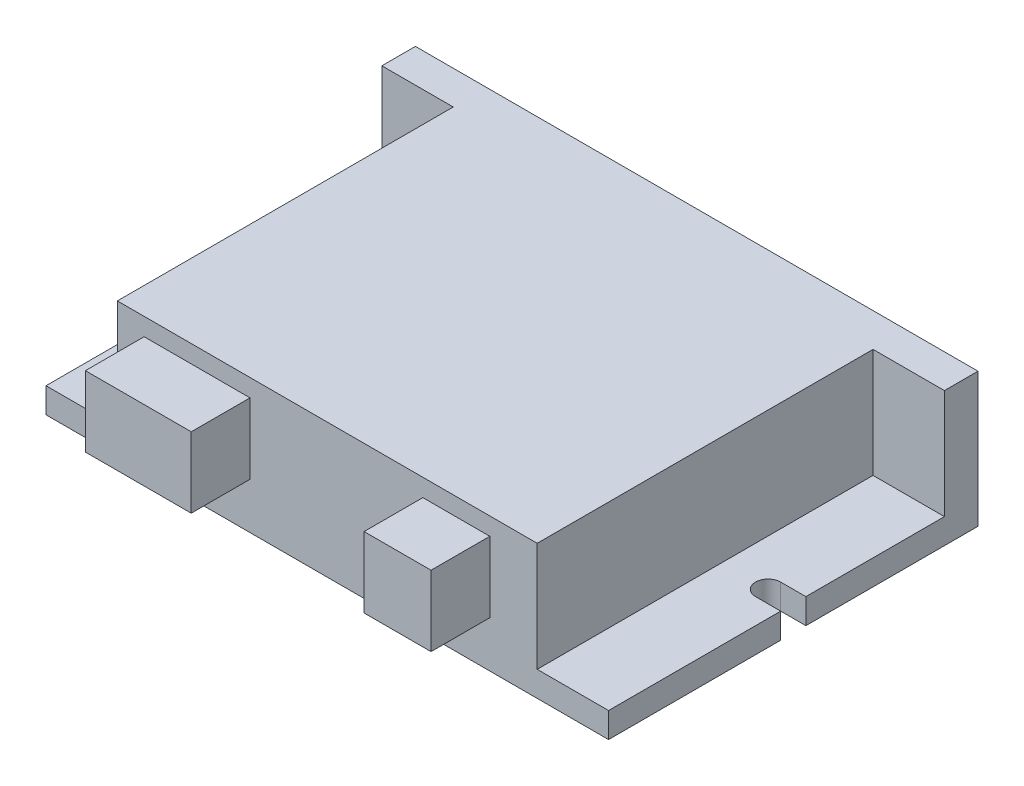
SolidWorks part; units mm, degrees
ref_plane "Front Plane" through (0, 0, 0) normal (0, 0, 1) x (1, 0, 0)
ref_plane "Top Plane" through (0, 0, 0) normal (0, 1, 0) x (1, 0, 0)
ref_plane "Right Plane" through (0, 0, 0) normal (1, 0, 0) x (0, 0, -1)
sketch "Sketch2" plane through (0, 0, 0) normal (0, 1, 0) x (1, 0, 0)
  line L1 (-42.545, -27.94) -> (42.545, -27.94)
  line L2 (-42.545, -27.94) -> (-42.545, 27.94)
  line L3 (-42.545, 27.94) -> (42.545, 27.94)
  line L4 (42.545, -27.94) -> (42.545, 27.94)
  line L5 (-42.545, -27.94) -> (42.545, 27.94) construction
  line L6 (-42.545, 27.94) -> (42.545, -27.94) construction
  point P0 (0, 0)
  dimension "D1" = 55.88
  dimension "D2" = 85.09
extrude "Boss-Extrude1" add sketch "Sketch2" along normal blind 3.81
sketch "Sketch3" plane through (0, 3.81, 0) normal (0, 1, 0) x (1, 0, 0)
  line L0 (-42.545, -27.94) -> (42.545, -27.94) construction
  line L1 (-31.75, -27.94) -> (31.75, -27.94)
  line L2 (-31.75, -27.94) -> (-31.75, 22.86)
  line L3 (-31.75, 22.86) -> (31.75, 22.86)
  line L4 (31.75, -27.94) -> (31.75, 22.86)
  point P6 (0, 22.86)
  dimension "D1" = 50.8
  dimension "D2" = 63.5
extrude "Boss-Extrude2" add sketch "Sketch3" along normal blind 16.51
sketch "Sketch4" plane through (0, 3.81, 0) normal (0, 1, 0) x (1, 0, 0)
  line L0 (42.545, -27.94) -> (42.545, 27.94) construction
  line L1 (-42.545, 27.94) -> (42.545, 27.94)
  line L2 (-42.545, 27.94) -> (-42.545, 22.86)
  line L3 (-42.545, 22.86) -> (42.545, 22.86)
  line L4 (42.545, 27.94) -> (42.545, 22.86)
  line L5 (31.75, 22.86) -> (-31.75, 22.86) construction
extrude "Boss-Extrude3" add sketch "Sketch4" along normal up to surface (16.51 mm away) up to face at (0, 20.32, 2.54)
sketch "Sketch5" plane through (0, 3.81, 0) normal (0, 1, 0) x (1, 0, 0)
  line L0 (38.735, 1.905) -> (42.545, 1.905)
  line L1 (42.545, -27.94) -> (42.545, 22.86) construction
  line L2 (38.735, -1.905) -> (42.545, -1.905)
  line L3 (42.545, 1.905) -> (42.545, -1.905)
  line L4 (0, 36.9467) -> (0, -38.9863) construction
  line L5 (-42.545, 1.905) -> (-42.545, -1.905)
  line L6 (-38.735, -1.905) -> (-42.545, -1.905)
  line L7 (-38.735, 1.905) -> (-42.545, 1.905)
  arc A0 (38.735, 1.905) -> (38.735, -1.905) centre (38.735, 0) ccw
  arc A1 (-38.735, 1.905) -> (-38.735, -1.905) centre (-38.735, 0) cw
  dimension "D1" = 1.905
  dimension "D2" = 3.81
extrude "Cut-Extrude1" cut sketch "Sketch5" against normal through all both and the other way through all
sketch "Sketch6" plane through (0, 0, 27.94) normal (0, 0, 1) x (1, 0, 0)
  line L0 (-42.545, 0) -> (42.545, 0) construction
  line L1 (-27.6993, 6.985) -> (-11.6856, 6.985)
  line L2 (-27.6993, 6.985) -> (-27.6993, 17.653)
  line L3 (-27.6993, 17.653) -> (-11.6856, 17.653)
  line L4 (-11.6856, 6.985) -> (-11.6856, 17.653)
  line L5 (14.4556, 6.985) -> (24.5831, 6.985)
  line L6 (14.4556, 6.985) -> (14.4556, 17.653)
  line L7 (14.4556, 17.653) -> (24.5831, 17.653)
  line L8 (24.5831, 6.985) -> (24.5831, 17.653)
  point P10 (0, 0)
  point P11 (0, 0)
  point P12 (0, 0)
  dimension "D1" = 6.985
  dimension "D2" = 10.668
extrude "Boss-Extrude4" add sketch "Sketch6" along normal blind 8.89
